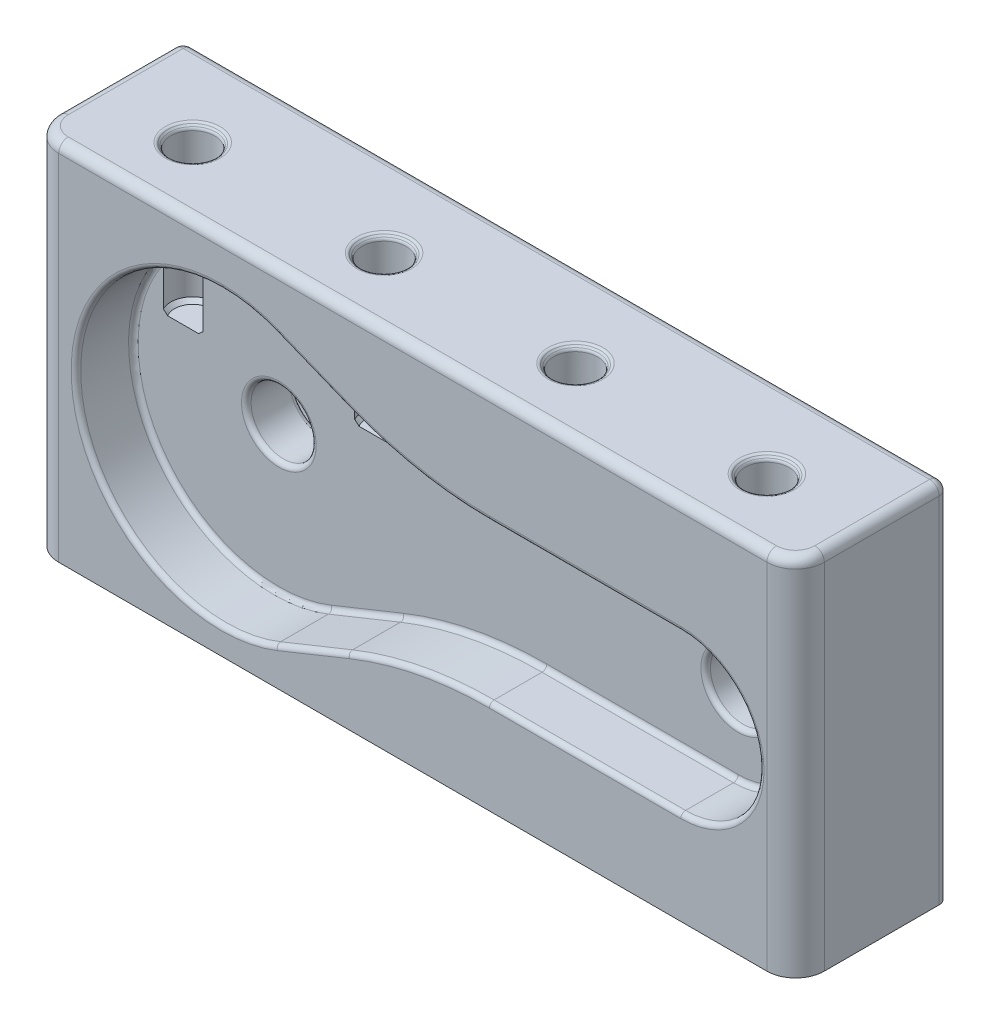
SolidWorks part; units mm, degrees
ref_plane "Front Plane" through (0, 0, 0) normal (0, 0, 1) x (1, 0, 0)
ref_plane "Top Plane" through (0, 0, 0) normal (0, 1, 0) x (1, 0, 0)
ref_plane "Right Plane" through (0, 0, 0) normal (1, 0, 0) x (0, 0, -1)
sketch "Sketch2" plane through (0, 0, 0) normal (0, 0, 1) x (1, 0, 0)
  line L1 (-20, -9.5) -> (20, -9.5)
  line L2 (-20, -9.5) -> (-20, 9.5)
  line L3 (-20, 9.5) -> (20, 9.5)
  line L4 (20, -9.5) -> (20, 9.5)
  line L5 (-20, -9.5) -> (20, 9.5) construction
  line L6 (-20, 9.5) -> (20, -9.5) construction
  point P0 (0, 0)
  dimension "D1" = 40
  dimension "D2" = 19
extrude "Boss-Extrude1" add sketch "Sketch2" along normal blind 8
fillet "Fillet1" radius 1.5 2 edges at (20, 0, 8) (-20, 0, 8)
sketch "Sketch5" plane through (0, 9.5, 0) normal (0, 1, 0) x (1, 0, 0)
  line L0 (18.5, -8) -> (-18.5, -8) construction
  line L1 (-20, -6.5) -> (-20, 0) construction
  circle A0 centre (-15, -4.5) radius 1.15
  circle A1 centre (-5, -4.5) radius 1.15
  circle A2 centre (5, -4.5) radius 1.15
  circle A3 centre (15, -4.5) radius 1.15
  dimension "D1" = 2.3
  dimension "D2" = 3.5
  dimension "D3" = 5
  dimension "D5" = 10
  dimension "D4" = 4
extrude "Cut-Extrude3" cut sketch "Sketch5" against normal blind 8
chamfer "Chamfer1" distance 0.2 angle 45 8 edges at (15, 9.5, 5.65) (15, 1.5, 5.65) (5, 9.5, 5.65) (5, 1.5, 5.65) (-5, 9.5, 5.65) (-5, 1.5, 5.65) (-15, 9.5, 5.65) (-15, 1.5, 5.65)
fillet "Fillet3" radius 0.2 8 edges at (-15, 9.3, 3.35) (-15, 9.5, 3.15) (-5, 9.3, 3.35) (-5, 9.5, 3.15) (5, 9.3, 3.35) (5, 9.5, 3.15) (15, 9.3, 3.35) (15, 9.5, 3.15)
fillet "Fillet2" radius 0.5 8 edges at (20, 9.5, 3.25) (19.5607, 9.5, 7.5607) (-20, 9.5, 3.25) (-19.5607, 9.5, 7.5607) (0, 9.5, 8) (0, 9.5, 0) (20, 0, 0) (-20, 0, 0)
sketch "Sketch6" plane through (0, 0, 8) normal (0, 0, 1) x (1, 0, 0)
  line L0 (-18.5, -9.5) -> (18.5, -9.5) construction
  line L1 (-20, -9.5) -> (-20, 9) construction
  circle A0 centre (-10, -0.5) radius 1.7
  circle A1 centre (14, -0.5) radius 1.7
  dimension "D1" = 3.4
  dimension "D2" = 9
  dimension "D3" = 24
  dimension "D4" = 10
extrude "Cut-Extrude4" cut sketch "Sketch6" against normal through all
sketch "Sketch7" plane through (0, 0, 0) normal (0, 0, -1) x (-1, 0, 0)
  circle A0 centre (-14, -0.5) radius 3
  circle A1 centre (10, -0.5) radius 3
  dimension "D1" = 6
extrude "Cut-Extrude5" cut sketch "Sketch7" against normal blind 2.5
sketch "Sketch8" plane through (0, 0, 8) normal (0, 0, 1) x (1, 0, 0)
  line L0 (14, -4.6) -> (4, -4.6)
  line L1 (14, 3.6) -> (4, 3.6)
  line L2 (-7.1603, -7.5495) -> (-3.3982, -6.0341)
  line L3 (-10, -0.5) -> (14, -0.5) construction
  line L4 (-7.1603, 6.5495) -> (-3.3982, 5.0341)
  arc A0 (-7.1603, 6.5495) -> (-7.1603, -7.5495) centre (-10, -0.5) ccw
  arc A1 (14, -4.6) -> (14, 3.6) centre (14, -0.5) ccw
  arc A3 (-3.3982, -6.0341) -> (4, -4.6) centre (4, -24.4) cw
  arc A4 (-3.3982, 5.0341) -> (4, 3.6) centre (4, 23.4) ccw
  dimension "D1" = 15.2
  dimension "D2" = 8.2
  dimension "D4" = 19.8
  dimension "D3" = 10
  dimension "D5" = 158.059
extrude "Cut-Extrude6" cut sketch "Sketch8" against normal blind 3
fillet "Fillet5" radius 0.25 17 edges at (-6.598, 6.323, 5) (17.9624, -1.5531, 5) (9, -4.6, 5) (0.232, -4.9618, 5) (-5.2792, -6.7918, 5) (-5.2792, 5.7918, 8) (0.232, 3.9618, 8) (9, 3.6, 8) (18.1, -0.5, 8) (9, -4.6, 8) (0.232, -4.9618, 8) (-5.2792, -6.7918, 8) (-13, -0.5, 0) (11, -0.5, 0) (-10.6294, 7.0739, 5) (-16.0489, -5.1011, 5) (-17.6, -0.5, 8)
fillet "Fillet6" radius 0.25 4 edges at (15.7, -0.5, 5) (12.3, -0.5, 2.5) (-8.3, -0.5, 5) (-11.7, -0.5, 2.5)
